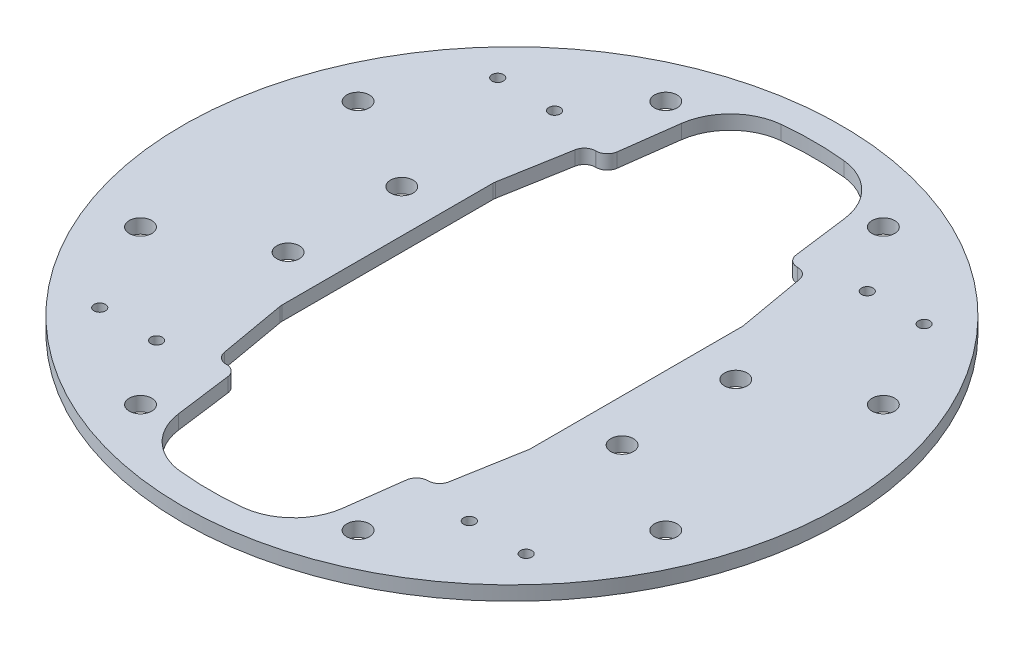
SolidWorks part; units mm, degrees
material "Plain Carbon Steel"
ref_plane "Front Plane" through (0, 0, 0) normal (0, 0, 1) x (1, 0, 0)
ref_plane "Top Plane" through (0, 0, 0) normal (0, 1, 0) x (1, 0, 0)
ref_plane "Right Plane" through (0, 0, 0) normal (1, 0, 0) x (0, 0, -1)
sketch "Sketch1" plane through (0, 0, 0) normal (0, 1, 0) x (1, 0, 0)
  line L0 (0, 0) -> (0, 219.4614) construction
  line L7 (-36.6127, 112.2677) -> (-40.5251, 82.55)
  line L8 (-55.5625, 47.625) -> (-55.5625, -47.625)
  line L14 (55.5625, 47.625) -> (55.5625, -47.625)
  line L15 (36.6127, 112.2677) -> (40.5251, 82.55)
  line L17 (0, 0) -> (-134.4697, 0) construction
  line L18 (-40.5251, 82.55) -> (-49.4043, 82.55)
  line L19 (-49.4043, 82.55) -> (-55.5625, 47.625)
  line L20 (40.5251, 82.55) -> (49.4043, 82.55)
  line L21 (49.4043, 82.55) -> (55.5625, 47.625)
  line L22 (49.4043, -82.55) -> (55.5625, -47.625)
  line L23 (40.5251, -82.55) -> (49.4043, -82.55)
  line L24 (-49.4043, -82.55) -> (-55.5625, -47.625)
  line L25 (-40.5251, -82.55) -> (-49.4043, -82.55)
  line L26 (36.6127, -112.2677) -> (40.5251, -82.55)
  line L27 (-36.6127, -112.2677) -> (-40.5251, -82.55)
  line L28 (34.2067, -130.5429) -> (35.3333, -121.9859) construction
  line L29 (35.3333, -121.9859) -> (36.6127, -112.2677) construction
  circle A0 centre (0, 0) radius 147.2413
  arc A1 (14.0801, 134.2137) -> (-14.0801, 134.2137) centre (0, 0) ccw
  arc A2 (14.0801, -134.2137) -> (0, -134.9502) centre (0, 0) cw
  arc A3 (34.2067, 130.5429) -> (0, 134.9502) centre (0, 0) ccw
  arc A4 (14.0801, -134.2137) -> (-14.0801, -134.2137) centre (0, 0) cw
  circle A6 centre (48.6008, 117.3327) radius 4.7625 construction
  circle A7 centre (117.3327, 48.6008) radius 4.7625 construction
  circle A8 centre (117.3327, -48.6008) radius 4.7625 construction
  circle A9 centre (48.6008, -117.3327) radius 4.7625 construction
  circle A10 centre (-48.6008, -117.3327) radius 4.7625 construction
  circle A11 centre (-117.3327, -48.6008) radius 4.7625 construction
  circle A12 centre (-117.3327, 48.6008) radius 4.7625 construction
  circle A13 centre (-48.6008, 117.3327) radius 4.7625 construction
  circle A14 centre (0, 0) radius 127 construction
  arc A15 (-14.0801, -134.2137) -> (-36.6127, -112.2677) centre (-11.43, -108.9523) cw
  arc A16 (36.6127, 112.2677) -> (14.0801, 134.2137) centre (11.43, 108.9523) ccw
  arc A17 (-14.0801, 134.2137) -> (-36.6127, 112.2677) centre (-11.43, 108.9523) ccw
  arc A18 (36.6127, -112.2677) -> (14.0801, -134.2137) centre (11.43, -108.9523) cw
  arc A19 (34.2067, -130.5429) -> (14.0801, -134.2137) centre (0, 0) cw construction
  arc A20 (34.2067, -130.5429) -> (14.0801, -134.2137) centre (0, 0) cw construction
  point P9 (-55.5625, 0)
  point P27 (55.5625, 0)
  point P45 (0, 0)
  point P46 (-34.2067, -130.5429)
  point P53 (-34.2067, 130.5429)
  point P57 (55.5625, 48.6008)
  dimension "D1" = 294.4825
  dimension "D4" = 134.9502
  dimension "D5" = 8
  dimension "D6" = 9.525
  dimension "D7" = 254
  dimension "D8" = 25.4
  dimension "D10" = 165.1
  dimension "D2" = 111.125
  dimension "D3" = 7.5
  dimension "D9" = 22.86
  dimension "D11" = 10
  dimension "D12" = 34.925
extrude "Boss-Extrude1" add sketch "Sketch1" along normal blind 6.35 contours A0 A2 A4 L27 L25 L24 L8 L19 L18 L7 A1 L15 L20 L21 L14 L22 L23 L26
hole_wizard "3/8 Clearance Hole1" positions "Sketch4" profile "Sketch3" hole size "3/8" standard "ANSI Inch" end condition through all
sketch "Sketch4" plane through (0, 6.35, 0) normal (0, 1, 0) x (1, 0, 0)
  point P0 (-117.3327, 48.6008)
  point P3 (-48.6008, 117.3327)
  point P6 (48.6008, 117.3327)
  point P9 (117.3327, 48.6008)
  point P12 (117.3327, -48.6008)
  point P15 (48.6008, -117.3327)
  point P18 (-48.6008, -117.3327)
  point P21 (-117.3327, -48.6008)
sketch "Sketch3" plane through (-117.3327, 6.35, -48.6008) normal (1, 0, 0) x (0, 0, 1)
  line L0 (0, 0) -> (0, 6.35)
  line L1 (0, 6.35) -> (5.0419, 6.35)
  line L2 (5.0419, 6.35) -> (5.0419, 0)
  line L5 (5.0419, 0) -> (0, 0)
  line L11 (0, -6.35) -> (0, 107.95) construction
  dimension "Thru Hole Dia." = 10.0838
  dimension "Thru Hole Depth" = 6.35
sketch "Sketch6" plane through (0, 0, 0) normal (1, 0, 0) x (0, 0, -1)
  line L1 (-147.2413, 0) -> (147.2413, 0) construction
  line L2 (0, 0) -> (0, -32.8927) construction
  circle A0 centre (141.2875, -0.7937) radius 2.3813
  dimension "D1" = 1.5875
  dimension "D2" = 4.7625
  dimension "D3" = 282.575
revolve "Cut-Revolve1" cut sketch "Sketch6" angle 360 about L2
hole_wizard "3/8 Clearance Hole2" positions "Sketch9" profile "Sketch8" hole size "3/8" standard "ANSI Inch" end condition through all
sketch "Sketch9" plane through (0, 0, 0) normal (0, -1, 0) x (-1, 0, 0)
  line L1 (55.5625, 47.625) -> (55.5625, -47.625) construction
  line L2 (-55.5625, 47.625) -> (-55.5625, -47.625) construction
  point P0 (74.6125, -25.4)
  point P2 (74.6125, 25.4)
  point P4 (-74.6125, 25.4)
  point P6 (-74.6125, -25.4)
  dimension "D1" = 19.05
  dimension "D2" = 25.4
  dimension "D3" = 25.4
  dimension "D4" = 19.05
sketch "Sketch8" plane through (-74.6125, 0, 25.4) normal (1, 0, 0) x (0, 0, -1)
  line L0 (0, 0) -> (0, 6.35)
  line L1 (0, 6.35) -> (5.0419, 6.35)
  line L2 (5.0419, 6.35) -> (5.0419, 0)
  line L5 (5.0419, 0) -> (0, 0)
  line L11 (0, -6.35) -> (0, 107.95) construction
  dimension "Thru Hole Dia." = 10.0838
  dimension "Thru Hole Depth" = 6.35
fillet "Fillet1" radius 5.08 12 edges at (-40.5251, 3.175, -82.55) (-49.4043, 3.175, -82.55) (-55.5625, 3.175, -47.625) (-55.5625, 3.175, 47.625) (-49.4043, 3.175, 82.55) (-40.5251, 3.175, 82.55) (40.5251, 3.175, 82.55) (49.4043, 3.175, 82.55) (55.5625, 3.175, 47.625) (55.5625, 3.175, -47.625) (49.4043, 3.175, -82.55) (40.5251, 3.175, -82.55)
hole_wizard "#7 (0.201) Diameter Hole1" positions "Sketch10" profile "Sketch11" hole size "#7" standard "ANSI Inch" end condition up to next
sketch "Sketch10" plane through (0, 6.35, 0) normal (0, 1, 0) x (1, 0, 0)
  line L0 (0, 0) -> (0, -50000) construction
  line L1 (-95.25, -88.9) -> (-69.85, 88.9) construction
  line L4 (-95.25, 88.9) -> (-69.85, -88.9) construction
  line L7 (-82.55, 0) -> (82.55, 0) construction
  line L10 (95.25, 88.9) -> (69.85, -88.9) construction
  line L11 (95.25, -88.9) -> (69.85, 88.9) construction
  point P0 (-69.85, -88.9)
  point P2 (-95.25, -88.9)
  point P4 (-95.25, 88.9)
  point P6 (-69.85, 88.9)
  point P22 (-82.55, 0)
  point P26 (-77.1971, 75.5961)
  point P27 (-93.1064, 76.2)
  point P29 (0, 0)
  point P34 (69.85, 88.9)
  point P35 (95.25, 88.9)
  point P36 (95.25, -88.9)
  point P37 (69.85, -88.9)
  dimension "D1" = 25.4
  dimension "D2" = 177.8
  dimension "D3" = 139.7
sketch "Sketch11" plane through (-69.85, 6.35, 88.9) normal (1, 0, 0) x (0, 0, 1)
  line L0 (0, 0) -> (0, 6.35)
  line L1 (0, 6.35) -> (2.5527, 6.35)
  line L2 (2.5527, 6.35) -> (2.5527, 0)
  line L5 (2.5527, 0) -> (0, 0)
  line L11 (0, -6.35) -> (0, 107.95) construction
  dimension "Thru Hole Dia." = 5.1054
  dimension "Thru Hole Depth" = 6.35
